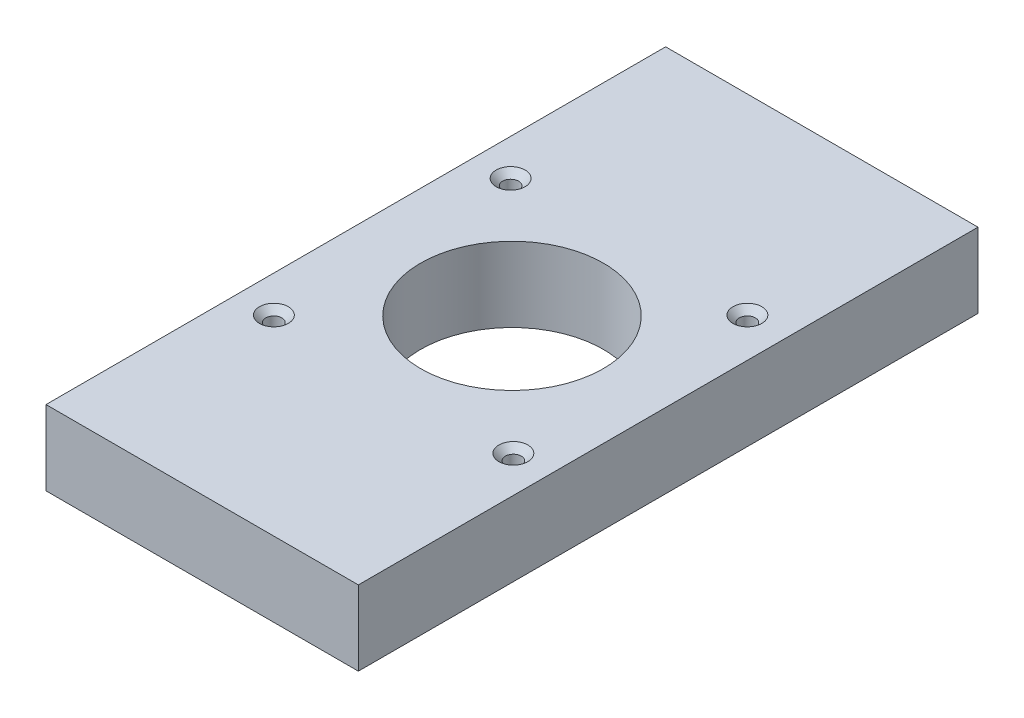
SolidWorks part; units mm, degrees
material "Alloy Steel (SS)"
ref_plane "Front Plane" through (0, 0, 0) normal (0, 0, 1) x (1, 0, 0)
ref_plane "Top Plane" through (0, 0, 0) normal (0, 1, 0) x (1, 0, 0)
ref_plane "Right Plane" through (0, 0, 0) normal (1, 0, 0) x (0, 0, -1)
sketch "Sketch1" plane through (0, 0, 0) normal (0, 1, 0) x (1, 0, 0)
  line L1 (-15.4153, -30.5791) -> (15.4153, -30.5791)
  line L2 (-15.4153, -30.5791) -> (-15.4153, 30.5791)
  line L3 (-15.4153, 30.5791) -> (15.4153, 30.5791)
  line L4 (15.4153, -30.5791) -> (15.4153, 30.5791)
  line L5 (-15.4153, -30.5791) -> (15.4153, 30.5791) construction
  line L6 (-15.4153, 30.5791) -> (15.4153, -30.5791) construction
  point P0 (0, 0)
  dimension "D1" = 30.8305
  dimension "D2" = 61.1581
extrude "Boss-Extrude1" add sketch "Sketch1" along normal blind 7.3762
sketch "Sketch2" plane through (0, 7.3762, 0) normal (0, 1, 0) x (1, 0, 0)
  circle A0 centre (0, 0) radius 9.0221
  dimension "D1" = 18.0442
extrude "Cut-Extrude1" cut sketch "Sketch2" against normal through all
sketch "Sketch3" plane through (0, 7.3762, 0) normal (0, 1, 0) x (1, 0, 0)
  line L0 (-15.4153, 30.5791) -> (-15.4153, -30.5791) construction
  line L1 (15.4153, 30.5791) -> (-15.4153, 30.5791) construction
  line L2 (15.4153, -30.5791) -> (15.4153, 30.5791) construction
  line L3 (-4.0569, 0) -> (4.0569, 0) construction
  circle A0 centre (-11.8186, 26.9824) radius 0.7937
  circle A1 centre (11.8186, 26.9824) radius 0.7937
  circle A2 centre (11.8186, -26.9824) radius 0.7937
  circle A3 centre (-11.8186, -26.9824) radius 0.7937
  dimension "D1" = 1.5875
  dimension "D2" = 1.5875
  dimension "D3" = 3.5966
  dimension "D4" = 3.5966
  dimension "D5" = 3.5966
  dimension "D6" = 3.5966
sketch "Sketch6" plane through (0, 7.3762, 0) normal (0, 1, 0) x (1, 0, 0)
  line L0 (-15.4153, 30.5791) -> (-15.4153, -30.5791) construction
  line L1 (15.4153, -30.5791) -> (15.4153, 30.5791) construction
  line L2 (-11.8186, 11.684) -> (11.5494, 11.684) construction
  line L3 (-0.1346, 11.684) -> (0, -30.5791) construction
  line L4 (-15.4153, -30.5791) -> (15.4153, -30.5791) construction
  point P0 (-11.8186, 11.684)
  point P1 (11.5494, 11.684)
  point P2 (11.8186, -11.684)
  point P3 (-11.8186, -11.684)
  dimension "D1" = 23.368
  dimension "D2" = 3.5966
  dimension "D3" = 23.368
  dimension "D4" = 3.5966
  dimension "D5" = 23.368
  dimension "D6" = 3.5966
  dimension "D7" = 11.684
hole_wizard "1/16 (0.0625) Diameter Hole2" positions "Sketch7" profile "Sketch8" hole size "1/16" standard "ANSI Inch" end condition through all
sketch "Sketch7" plane through (0, 7.3762, 0) normal (0, 1, 0) x (1, 0, 0)
  point P0 (-11.8186, 11.684)
  point P3 (11.5494, 11.684)
  point P6 (11.8186, -11.684)
  point P9 (-11.8186, -11.684)
sketch "Sketch8" plane through (-11.8186, 7.3762, -11.684) normal (1, 0, 0) x (0, 0, 1)
  line L0 (0, 0) -> (0, 7.3762)
  line L1 (0, 7.3762) -> (0.7937, 7.3762)
  line L2 (0.7937, 7.3762) -> (0.7937, 0.635)
  line L3 (0.7937, 0.635) -> (1.4287, 0)
  line L5 (1.4287, 0) -> (0, 0)
  line L6 (-0.7937, 0.635) -> (-1.4287, 0) construction
  line L11 (0, -6.35) -> (0, 107.95) construction
  dimension "Thru Hole Dia." = 1.5875
  dimension "Thru Hole Depth" = 7.3762
  dimension "Near C'Sink Dia." = 2.8575
  dimension "Near C'Sink Angle" = 90
